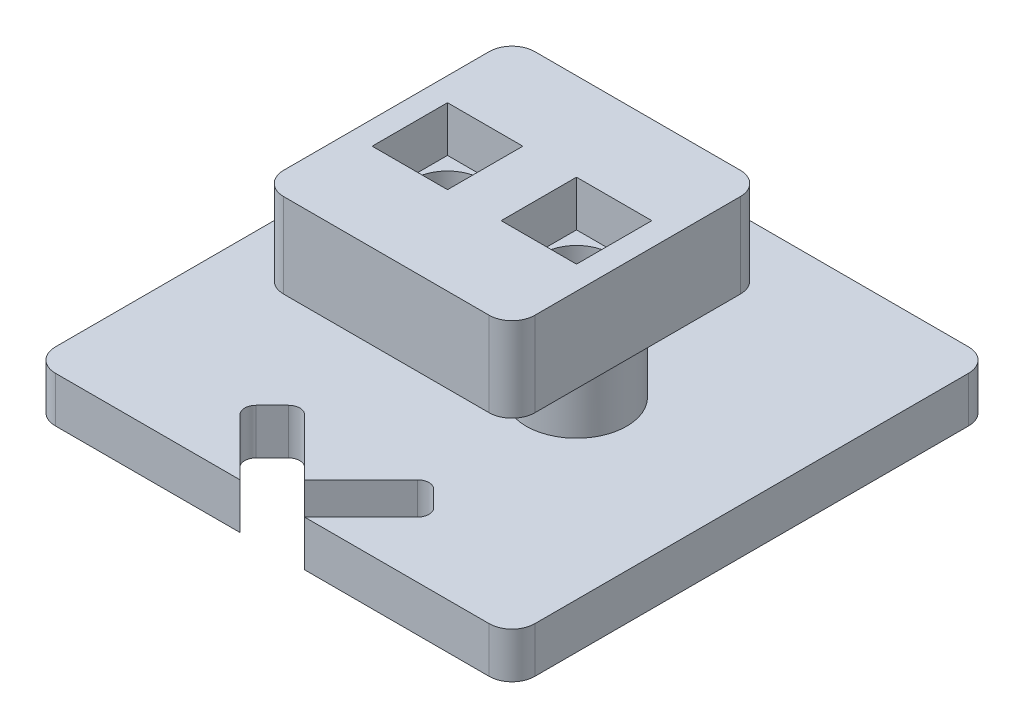
SolidWorks part; units mm, degrees
ref_plane "Front Plane" through (0, 0, 0) normal (0, 0, 1) x (1, 0, 0)
ref_plane "Top Plane" through (0, 0, 0) normal (0, 1, 0) x (1, 0, 0)
ref_plane "Right Plane" through (0, 0, 0) normal (1, 0, 0) x (0, 0, -1)
sketch "Sketch1" plane through (0, 0, 0) normal (0, 1, 0) x (1, 0, 0)
  line L1 (-5.5, -5.5) -> (5.5, -5.5)
  line L2 (-5.5, -5.5) -> (-5.5, 5.5)
  line L3 (-5.5, 5.5) -> (5.5, 5.5)
  line L4 (5.5, -5.5) -> (5.5, 5.5)
  line L5 (-5.5, -5.5) -> (5.5, 5.5) construction
  line L6 (-5.5, 5.5) -> (5.5, -5.5) construction
  point P0 (0, 0)
  dimension "D1" = 11
  dimension "D2" = 11
extrude "Boss-Extrude1" add sketch "Sketch1" along normal blind 3.7
fillet "Fillet1" radius 1 4 edges at (-5.5, 1.85, -5.5) (-5.5, 1.85, 5.5) (5.5, 1.85, -5.5) (5.5, 1.85, 5.5)
sketch "Sketch2" plane through (0, 3.7, 0) normal (0, 1, 0) x (1, 0, 0)
  line L0 (-2.825, 0) -> (2.825, 0) construction
  line L2 (-4.475, -1.65) -> (-1.175, -1.65)
  line L3 (-4.475, -1.65) -> (-4.475, 1.65)
  line L4 (-4.475, 1.65) -> (-1.175, 1.65)
  line L5 (-1.175, -1.65) -> (-1.175, 1.65)
  line L6 (-4.475, -1.65) -> (-1.175, 1.65) construction
  line L7 (-4.475, 1.65) -> (-1.175, -1.65) construction
  line L8 (1.175, -1.65) -> (4.475, -1.65)
  line L9 (1.175, -1.65) -> (1.175, 1.65)
  line L10 (1.175, 1.65) -> (4.475, 1.65)
  line L11 (4.475, -1.65) -> (4.475, 1.65)
  line L12 (1.175, -1.65) -> (4.475, 1.65) construction
  line L13 (1.175, 1.65) -> (4.475, -1.65) construction
  point P4 (0, 0)
  dimension "D1" = 3.3
  dimension "D2" = 3.3
  dimension "D3" = 3.3
  dimension "D4" = 3.3
  dimension "D5" = 5.65
extrude "Cut-Extrude1" cut sketch "Sketch2" against normal blind 2
sketch "Sketch4" plane through (0, 0, 0) normal (0, -1, 0) x (-1, 0, 0)
  line L0 (2.825, 0) -> (-2.825, 0) construction
  circle A0 centre (2.825, 0) radius 2.2
  circle A1 centre (-2.825, 0) radius 2.2
  point P4 (0, 0)
  point P8 (0, 0)
  dimension "D1" = 5.65
  dimension "D2" = 4.4
  dimension "D3" = 4.4
extrude "Boss-Extrude2" add sketch "Sketch4" along normal blind 5
sketch "Sketch5" plane through (0, -5, 0) normal (0, -1, 0) x (-1, 0, 0)
  line L1 (9.5, 10.5) -> (-9.5, 10.5)
  line L2 (10.5, 9.5) -> (10.5, -9.5)
  line L3 (9.5, -10.5) -> (-9.5, -10.5)
  line L4 (-10.5, 9.5) -> (-10.5, -9.5)
  line L5 (10.5, 10.5) -> (-10.5, -10.5) construction
  line L6 (10.5, -10.5) -> (-10.5, 10.5) construction
  arc A0 (10.5, -9.5) -> (9.5, -10.5) centre (9.5, -9.5) cw
  arc A1 (-10.5, -9.5) -> (-9.5, -10.5) centre (-9.5, -9.5) ccw
  arc A2 (-9.5, 10.5) -> (-10.5, 9.5) centre (-9.5, 9.5) ccw
  arc A3 (9.5, 10.5) -> (10.5, 9.5) centre (9.5, 9.5) cw
  point P0 (0, 0)
  dimension "D3" = 1
  dimension "D1" = 21
  dimension "D2" = 21
extrude "Boss-Extrude3" add sketch "Sketch5" against normal blind 2
sketch "Sketch3" plane through (0, 3.7, 0) normal (0, 1, 0) x (1, 0, 0)
  line L0 (-2.825, 0) -> (2.825, 0) construction
  circle A0 centre (-2.825, 0) radius 1.5
  circle A1 centre (2.825, 0) radius 1.5
  point P4 (0, 0)
  point P5 (0, 0)
  point P8 (0, 0)
  dimension "D2" = 3
  dimension "D3" = 3
  dimension "D1" = 5.65
extrude "Cut-Extrude2" cut sketch "Sketch3" against normal through all
sketch "Sketch7" plane through (0, -3, 0) normal (0, 1, 0) x (1, 0, 0)
  line L0 (9.5, -10.5) -> (-9.5, -10.5) construction
  line L1 (2.8284, -14.7426) -> (4.2426, -13.3284)
  line L2 (2.8284, -14.7426) -> (-3.8891, -8.0251)
  line L3 (-3.8891, -7.318) -> (-3.182, -6.6109)
  line L4 (4.2426, -13.3284) -> (-2.4749, -6.6109)
  line L5 (2.8284, -14.7426) -> (-2.8284, -6.2574) construction
  line L6 (-4.2426, -7.6716) -> (4.2426, -13.3284) construction
  line L8 (-4.2426, -13.3284) -> (-2.8284, -14.7426)
  line L9 (-4.2426, -13.3284) -> (2.4749, -6.6109)
  line L10 (3.182, -6.6109) -> (3.8891, -7.318)
  line L11 (-2.8284, -14.7426) -> (3.8891, -8.0251)
  line L12 (-4.2426, -13.3284) -> (4.2426, -7.6716) construction
  line L13 (2.8284, -6.2574) -> (-2.8284, -14.7426) construction
  arc A0 (-2.4749, -6.6109) -> (-3.182, -6.6109) centre (-2.8284, -6.9645) ccw
  arc A1 (3.8891, -7.318) -> (3.8891, -8.0251) centre (3.5355, -7.6716) cw
  arc A2 (3.182, -6.6109) -> (2.4749, -6.6109) centre (2.8284, -6.9645) ccw
  arc A3 (-3.8891, -7.318) -> (-3.8891, -8.0251) centre (-3.5355, -7.6716) ccw
  point P0 (0, -10.5)
  point P7 (0, -10.5)
  point P12 (-1.4142, -10.5)
  point P13 (1.4142, -10.5)
  line M12 (-9.5, -10.5) -> (9.5, -10.5)
  dimension "D7" = 0.5
  dimension "D8" = 0.5
  dimension "D1" = 2
  dimension "D2" = 45
  dimension "D3" = 2
  dimension "D4" = 45
  dimension "D5" = 4
  dimension "D6" = 4
extrude "Cut-Extrude3" cut sketch "Sketch7" against normal through all contours L10 A2 L9 L4 L11 A1 | L3 A3 L2 L9 L4 A0 | L9 L4 M12
equation "\"D2@Sketch2\"=\"D1@Sketch2\""
equation "\"D3@Sketch2\"=\"D1@Sketch2\""
equation "\"D4@Sketch2\"=\"D1@Sketch2\""
equation "\"D2@Sketch1\"=\"D1@Sketch1\""
equation "\"D3@Sketch3\"=\"D2@Sketch3\""
equation "\"D3@Sketch4\"=\"D2@Sketch4\""
equation "\"D2@Sketch5\"=\"D1@Sketch5\""
equation "\"D3@Sketch7\"=\"D1@Sketch7\""
equation "\"D6@Sketch7\"=\"D5@Sketch7\""
